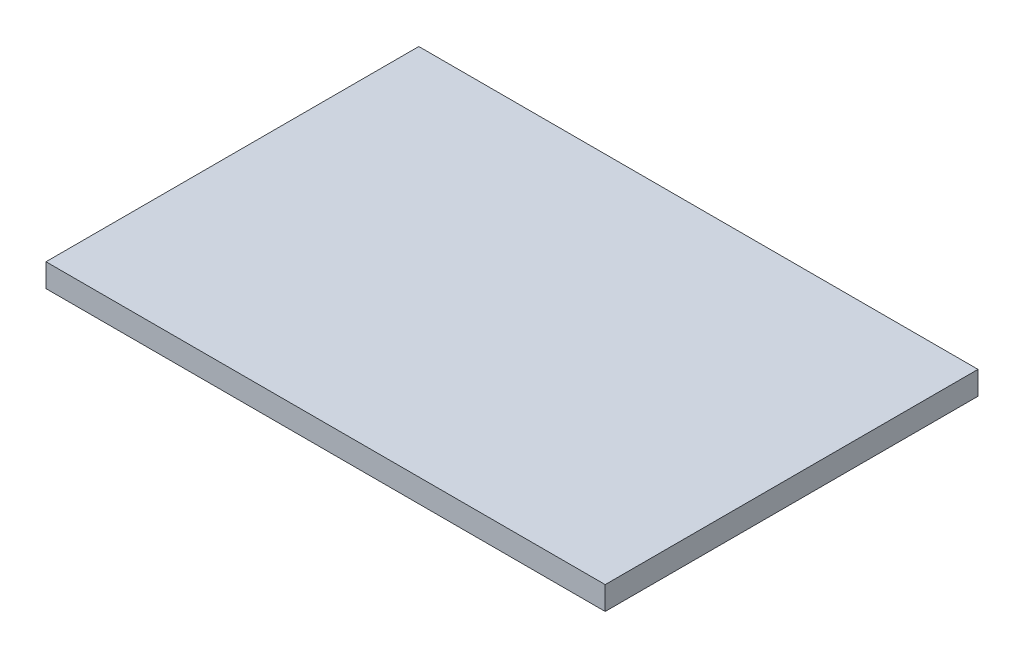
SolidWorks part; units mm, degrees
ref_plane "Front Plane" through (0, 0, 0) normal (0, 0, 1) x (1, 0, 0)
ref_plane "Top Plane" through (0, 0, 0) normal (0, 1, 0) x (1, 0, 0)
ref_plane "Right Plane" through (0, 0, 0) normal (1, 0, 0) x (0, 0, -1)
sketch "Sketch1" plane through (0, 0, 0) normal (0, 1, 0) x (1, 0, 0)
  line L0 (-228.6, 152.4) -> (228.6, -152.4) construction
  line L1 (-228.6, 152.4) -> (228.6, 152.4)
  line L2 (-228.6, 152.4) -> (-228.6, -152.4)
  line L3 (-228.6, -152.4) -> (228.6, -152.4)
  line L4 (228.6, 152.4) -> (228.6, -152.4)
  dimension "D1" = 457.2
  dimension "D2" = 304.8
extrude "Boss-Extrude1" add sketch "Sketch1" along normal blind 19.05
